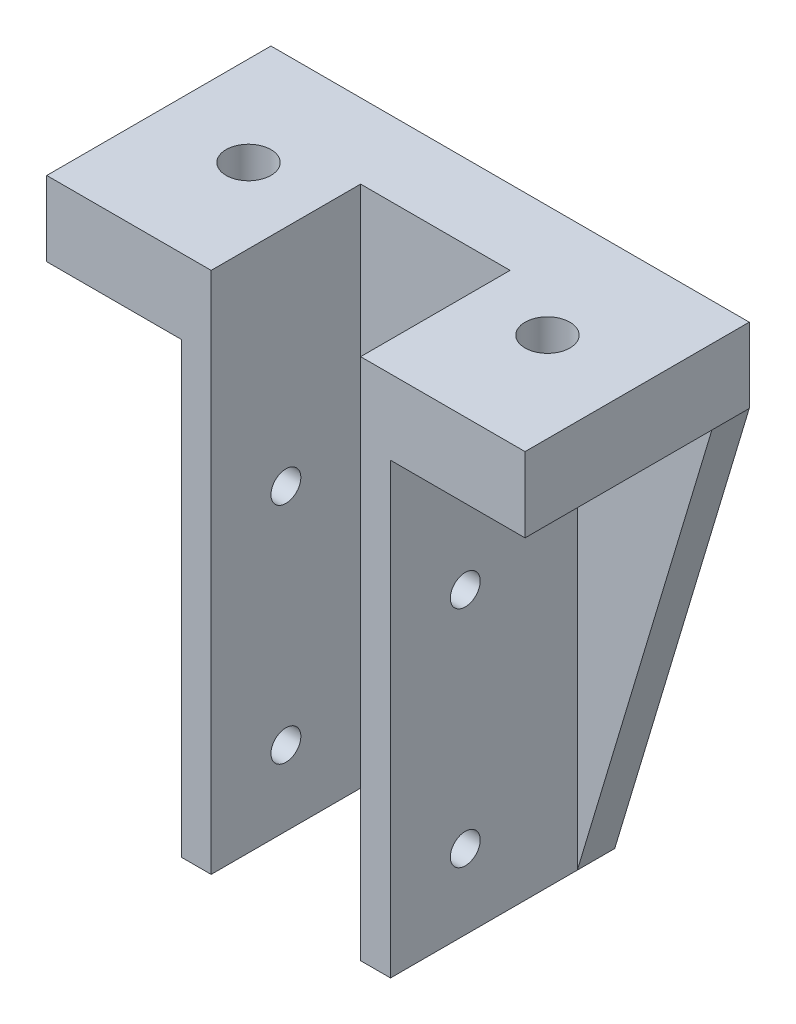
SolidWorks part; units mm, degrees
ref_plane "前视基准面" through (0, 0, 0) normal (0, 0, 1) x (1, 0, 0)
ref_plane "上视基准面" through (0, 0, 0) normal (0, 1, 0) x (1, 0, 0)
ref_plane "右视基准面" through (0, 0, 0) normal (1, 0, 0) x (0, 0, -1)
sketch "草图1" plane through (0, 0, 0) normal (0, 0, 1) x (1, 0, 0)
  line L1 (-14, 35) -> (14, 35)
  line L2 (-14, 35) -> (-14, -35)
  line L3 (-14, -35) -> (14, -35)
  line L4 (14, 35) -> (14, -35)
  line L5 (-14, 35) -> (14, -35) construction
  line L6 (-14, -35) -> (14, 35) construction
  point P0 (0, 0)
  dimension "D1" = 28
  dimension "D2" = 70
extrude "凸台-拉伸1" add sketch "草图1" along normal blind 30
sketch "草图2" plane through (0, 0, 30) normal (0, 0, 1) x (1, 0, 0)
  line L0 (14, 35) -> (-14, 35) construction
  line L1 (10, -35) -> (-10, -35)
  line L2 (10, -35) -> (10, 35)
  line L3 (10, 35) -> (-10, 35)
  line L4 (-10, -35) -> (-10, 35)
  line L5 (10, -35) -> (-10, 35) construction
  line L6 (10, 35) -> (-10, -35) construction
  point P0 (0, 0)
  dimension "D1" = 20
extrude "切除-拉伸1" cut sketch "草图2" against normal blind 20
sketch "草图4" plane through (0, 35, 0) normal (0, 1, 0) x (1, 0, 0)
  line L1 (14, 0) -> (32, 0)
  line L2 (14, 0) -> (14, -30)
  line L3 (14, -30) -> (32, -30)
  line L4 (32, 0) -> (32, -30)
  dimension "D1" = 30
  dimension "D2" = 18
extrude "凸台-拉伸2" add sketch "草图4" against normal blind 10
sketch "草图5" plane through (0, 35, 0) normal (0, 1, 0) x (1, 0, 0)
  line L0 (32, 0) -> (-14, 0) construction
  circle A0 centre (20, -15) radius 3
  dimension "D1" = 6
  dimension "D2" = 20
  dimension "D3" = 15
extrude "切除-拉伸2" cut sketch "草图5" against normal blind 19
sketch "草图6" plane through (0, 25, 0) normal (0, -1, 0) x (1, 0, 0)
  circle A0 centre (20, 15) radius 5.5
  dimension "D1" = 11
sketch "草图7" plane through (0, 0, 0) normal (0, 0, -1) x (-1, 0, 0)
  line L0 (-32, 25) -> (-14, -35)
  line L1 (-14, -35) -> (-14, 25)
  line L2 (-14, 25) -> (-32, 25)
extrude "凸台-拉伸3" add sketch "草图7" against normal blind 5
mirror "镜向1" about plane through (0, 0, 0) normal (1, 0, 0) of bodies 111
sketch "草图8" plane through (14, 0, 0) normal (1, 0, 0) x (0, 0, -1)
  line L0 (-30, -35) -> (-30, 25) construction
  line L1 (-5, 25) -> (-30, 25) construction
  circle A0 centre (-20, -25) radius 2
  circle A1 centre (-20, 5) radius 2
  point P4 (0, 0)
  dimension "D1" = 4
  dimension "D2" = 4
  dimension "D3" = 10
  dimension "D4" = 30
  dimension "D5" = 20
extrude "切除-拉伸3" cut sketch "草图8" against normal blind 98
sketch "草图9" plane through (0, 0, 10) normal (0, 0, 1) x (1, 0, 0)
  circle A0 centre (0, -20) radius 2
  circle A1 centre (0, 20) radius 2
  point P4 (0, 0)
  point P6 (0, 0)
  dimension "D1" = 4
  dimension "D2" = 4
  dimension "D3" = 20
  dimension "D4" = 20
extrude "切除-拉伸4" cut sketch "草图9" against normal blind 98
